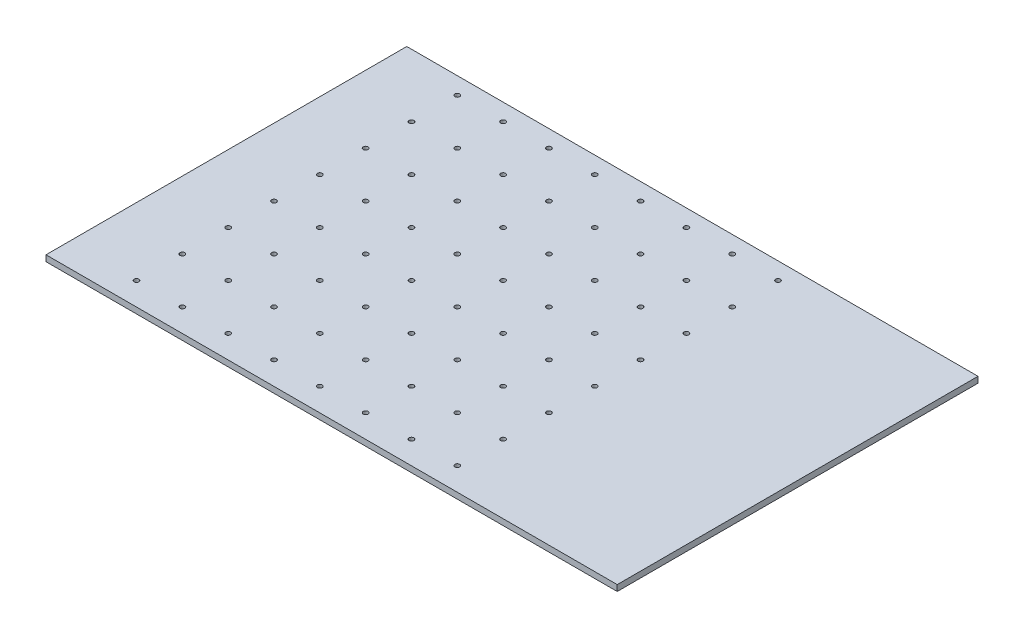
SolidWorks part; units mm, degrees
ref_plane "Front Plane" through (0, 0, 0) normal (0, 0, 1) x (1, 0, 0)
ref_plane "Top Plane" through (0, 0, 0) normal (0, 1, 0) x (1, 0, 0)
ref_plane "Right Plane" through (0, 0, 0) normal (1, 0, 0) x (0, 0, -1)
sketch "Sketch1" plane through (0, 0, 0) normal (0, 1, 0) x (1, 0, 0)
  line L1 (475, -300) -> (-475, -300)
  line L2 (475, -300) -> (475, 300)
  line L3 (475, 300) -> (-475, 300)
  line L4 (-475, -300) -> (-475, 300)
  line L5 (475, -300) -> (-475, 300) construction
  line L6 (475, 300) -> (-475, -300) construction
  point P0 (0, 0)
  dimension "D1" = 950
  dimension "D2" = 600
extrude "Boss-Extrude1" add sketch "Sketch1" along normal blind 10
sketch "Sketch2" plane through (0, 10, 0) normal (0, 1, 0) x (1, 0, 0)
  line L0 (-91, 300) -> (-91, -300) construction
  line L1 (475, 300) -> (-475, 300) construction
  line L2 (-475, -300) -> (475, -300) construction
  line L3 (-475, 300) -> (-475, -300) construction
  line L5 (209, -300) -> (-391, -300) construction
  line L6 (209, -300) -> (209, 300) construction
  line L7 (209, 300) -> (-391, 300) construction
  line L8 (-391, -300) -> (-391, 300) construction
  line L9 (209, -300) -> (-391, 300) construction
  line L10 (209, 300) -> (-391, -300) construction
  circle A0 centre (-362.7, 271.7) radius 4
  circle A14 centre (-286.5, 271.7) radius 4
  circle A15 centre (-210.3, 271.7) radius 4
  circle A16 centre (-134.1, 271.7) radius 4
  circle A17 centre (-57.9, 271.7) radius 4
  circle A18 centre (18.3, 271.7) radius 4
  circle A19 centre (94.5, 271.7) radius 4
  circle A20 centre (170.7, 271.7) radius 4
  circle A21 centre (-362.7, 195.5) radius 4
  circle A22 centre (-286.5, 195.5) radius 4
  circle A23 centre (-210.3, 195.5) radius 4
  circle A24 centre (-134.1, 195.5) radius 4
  circle A25 centre (18.3, 195.5) radius 4
  circle A26 centre (-57.9, 195.5) radius 4
  circle A27 centre (94.5, 195.5) radius 4
  circle A28 centre (170.7, 195.5) radius 4
  circle A29 centre (-362.7, 119.3) radius 4
  circle A30 centre (-286.5, 119.3) radius 4
  circle A31 centre (-210.3, 119.3) radius 4
  circle A32 centre (-134.1, 119.3) radius 4
  circle A33 centre (18.3, 119.3) radius 4
  circle A34 centre (-57.9, 119.3) radius 4
  circle A35 centre (94.5, 119.3) radius 4
  circle A36 centre (170.7, 119.3) radius 4
  circle A37 centre (-362.7, 43.1) radius 4
  circle A38 centre (-286.5, 43.1) radius 4
  circle A39 centre (-210.3, 43.1) radius 4
  circle A40 centre (-134.1, 43.1) radius 4
  circle A41 centre (18.3, 43.1) radius 4
  circle A42 centre (-57.9, 43.1) radius 4
  circle A43 centre (94.5, 43.1) radius 4
  circle A44 centre (170.7, 43.1) radius 4
  circle A45 centre (-362.7, -33.1) radius 4
  circle A46 centre (-286.5, -33.1) radius 4
  circle A47 centre (-210.3, -33.1) radius 4
  circle A48 centre (-134.1, -33.1) radius 4
  circle A49 centre (18.3, -33.1) radius 4
  circle A50 centre (-57.9, -33.1) radius 4
  circle A51 centre (94.5, -33.1) radius 4
  circle A52 centre (170.7, -33.1) radius 4
  circle A53 centre (-362.7, -109.3) radius 4
  circle A54 centre (-286.5, -109.3) radius 4
  circle A55 centre (-210.3, -109.3) radius 4
  circle A56 centre (-134.1, -109.3) radius 4
  circle A57 centre (18.3, -109.3) radius 4
  circle A58 centre (-57.9, -109.3) radius 4
  circle A59 centre (94.5, -109.3) radius 4
  circle A60 centre (170.7, -109.3) radius 4
  circle A61 centre (-362.7, -185.5) radius 4
  circle A62 centre (-286.5, -185.5) radius 4
  circle A63 centre (-210.3, -185.5) radius 4
  circle A64 centre (-134.1, -185.5) radius 4
  circle A65 centre (18.3, -185.5) radius 4
  circle A66 centre (-57.9, -185.5) radius 4
  circle A67 centre (94.5, -185.5) radius 4
  circle A68 centre (170.7, -185.5) radius 4
  circle A69 centre (-362.7, -261.7) radius 4
  circle A70 centre (-286.5, -261.7) radius 4
  circle A71 centre (-210.3, -261.7) radius 4
  circle A72 centre (-134.1, -261.7) radius 4
  circle A73 centre (18.3, -261.7) radius 4
  circle A74 centre (-57.9, -261.7) radius 4
  circle A75 centre (94.5, -261.7) radius 4
  circle A76 centre (170.7, -261.7) radius 4
  point P8 (-91, 0)
  dimension "D3" = 8
  dimension "D1" = 384
  dimension "D2" = 600
  dimension "D4" = 28.3
  dimension "D5" = 28.3
  dimension "D6" = 8
  dimension "D7" = 8
extrude "Cut-Extrude1" cut sketch "Sketch2" against normal blind 10
